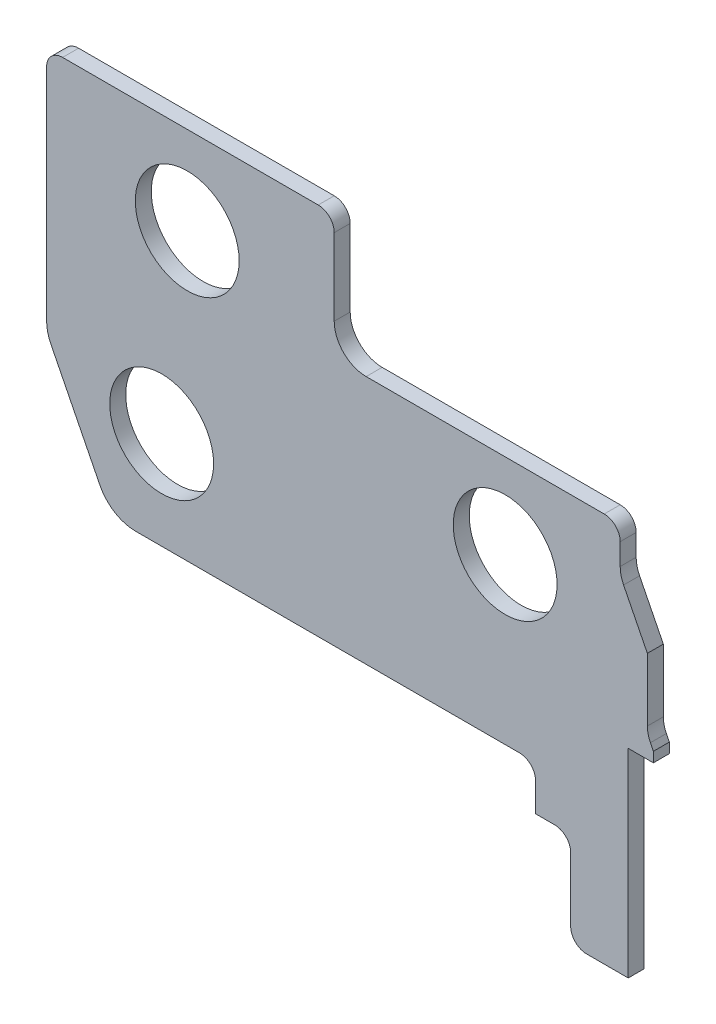
SolidWorks part; units mm, degrees
ref_plane "Front Plane" through (0, 0, 0) normal (0, 0, 1) x (1, 0, 0)
ref_plane "Top Plane" through (0, 0, 0) normal (0, 1, 0) x (1, 0, 0)
ref_plane "Right Plane" through (0, 0, 0) normal (1, 0, 0) x (0, 0, -1)
sketch "Sketch1" plane through (0, 0, 0) normal (0, 0, 1) x (1, 0, 0)
  line L34 (-77.5032, 240.0429) -> (-77.5032, 243.9841)
  line L35 (-77.5032, 243.9841) -> (-78.9904, 246.9452)
  line L36 (-79.2032, 247.8429) -> (-79.2032, 249.1873)
  line L37 (-80.2032, 250.1873) -> (-95.1032, 250.1873)
  line L38 (-97.1032, 252.1873) -> (-97.1032, 256.9873)
  line L39 (-98.1032, 257.9873) -> (-114.1032, 257.9873)
  line L40 (-115.1032, 256.9873) -> (-115.1032, 243.1984)
  line L41 (-114.8372, 242.0763) -> (-111.7678, 235.9652)
  line L42 (-109.5338, 234.5873) -> (-85.5032, 234.5873)
  line L43 (-84.5032, 233.5873) -> (-84.5032, 231.7873)
  line L44 (-84.5032, 231.7873) -> (-83.3032, 231.7873)
  line L45 (-82.3032, 230.7873) -> (-82.3032, 226.7873)
  line L46 (-81.3032, 225.7873) -> (-78.7, 225.7873)
  line L47 (-78.7, 225.7873) -> (-78.7, 238.2363)
  line L48 (-78.7, 238.2363) -> (-77.1252, 238.2363)
  line L49 (-77.1252, 238.2363) -> (-77.1252, 238.8637)
  line L50 (-77.1252, 238.8637) -> (-77.3117, 239.235)
  circle A14 centre (-107.9032, 240.6873) radius 3.25
  circle A15 centre (-86.4032, 244.8873) radius 3.25
  circle A16 centre (-106.3032, 252.4873) radius 3.25
  arc A22 (-77.5032, 240.0429) -> (-77.3117, 239.235) centre (-75.7032, 240.0429) ccw
  arc A23 (-79.2032, 247.8429) -> (-78.9904, 246.9452) centre (-77.2032, 247.8429) ccw
  arc A24 (-79.2032, 249.1873) -> (-80.2032, 250.1873) centre (-80.2032, 249.1873) ccw
  arc A25 (-97.1032, 252.1873) -> (-95.1032, 250.1873) centre (-95.1032, 252.1873) ccw
  arc A26 (-97.1032, 256.9873) -> (-98.1032, 257.9873) centre (-98.1032, 256.9873) ccw
  arc A27 (-114.1032, 257.9873) -> (-115.1032, 256.9873) centre (-114.1032, 256.9873) ccw
  arc A28 (-115.1032, 243.1984) -> (-114.8372, 242.0763) centre (-112.6032, 243.1984) ccw
  arc A29 (-111.7678, 235.9652) -> (-109.5338, 234.5873) centre (-109.5338, 237.0873) ccw
  arc A30 (-84.5032, 233.5873) -> (-85.5032, 234.5873) centre (-85.5032, 233.5873) ccw
  arc A31 (-82.3032, 230.7873) -> (-83.3032, 231.7873) centre (-83.3032, 230.7873) ccw
  arc A32 (-82.3032, 226.7873) -> (-81.3032, 225.7873) centre (-81.3032, 226.7873) ccw
extrude "Boss-Extrude1" add sketch "Sketch1" along normal blind 1
